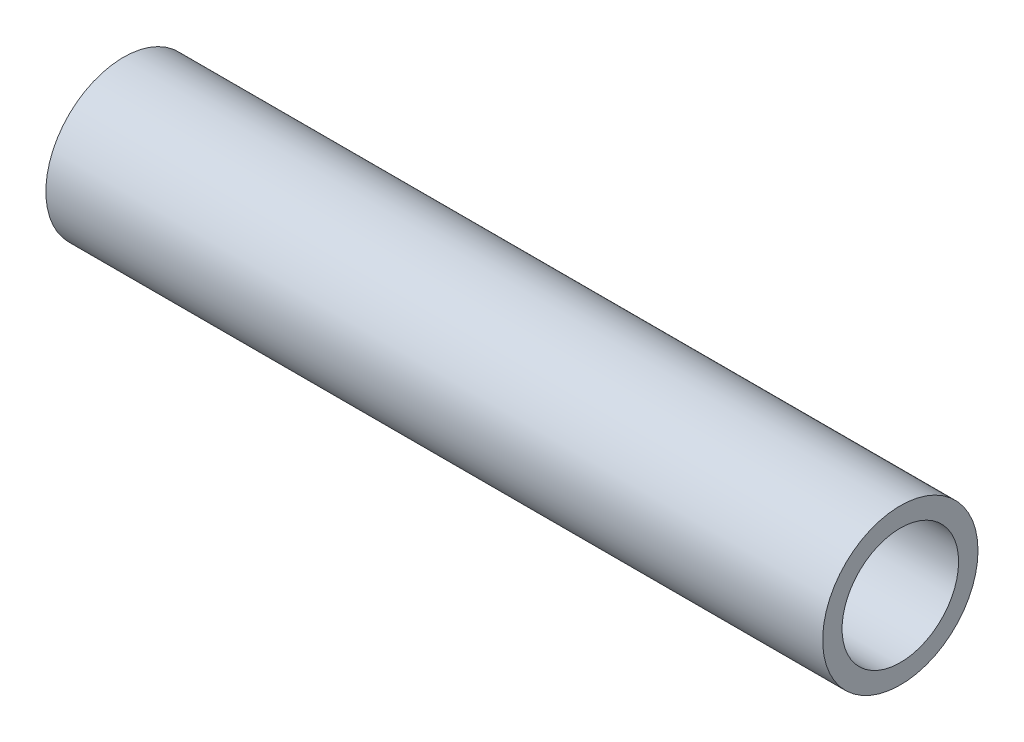
SolidWorks part; units mm, degrees
ref_plane "前视基准面" through (0, 0, 0) normal (0, 0, 1) x (1, 0, 0)
ref_plane "上视基准面" through (0, 0, 0) normal (0, 1, 0) x (1, 0, 0)
ref_plane "右视基准面" through (0, 0, 0) normal (1, 0, 0) x (0, 0, -1)
other "Configuration Table"
sketch "草图1" plane through (0, 0, 0) normal (1, 0, 0) x (0, 0, -1)
  circle A0 centre (0, 0) radius 1.5
  circle A1 centre (0, 0) radius 2
  dimension "D1" = 3
  dimension "D2" = 4
extrude "凸台-拉伸1" add sketch "草图1" along normal blind 20
